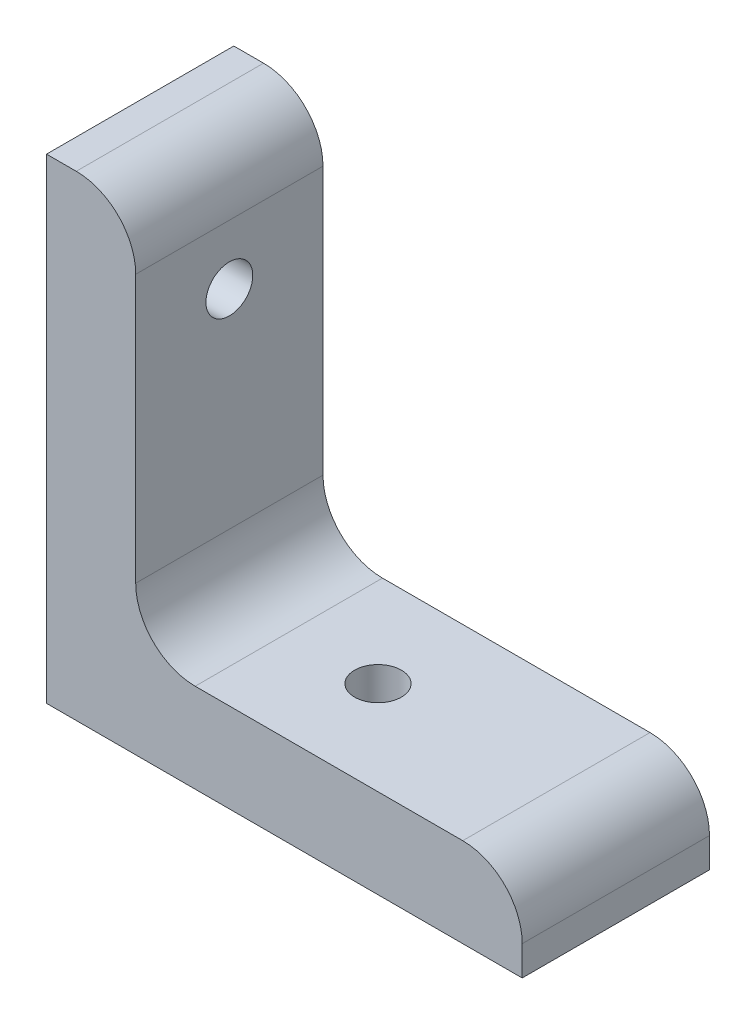
SolidWorks part; units mm, degrees
ref_plane "Front Plane" through (0, 0, 0) normal (0, 0, 1) x (1, 0, 0)
ref_plane "Top Plane" through (0, 0, 0) normal (0, 1, 0) x (1, 0, 0)
ref_plane "Right Plane" through (0, 0, 0) normal (1, 0, 0) x (0, 0, -1)
sketch "Sketch1" plane through (0, 0, 0) normal (0, 0, 1) x (1, 0, 0)
  line L0 (0, 0) -> (0, 50.8)
  line L1 (0, 50.8) -> (9.525, 50.8)
  line L2 (9.525, 50.8) -> (9.525, 9.525)
  line L3 (9.525, 9.525) -> (50.8, 9.525)
  line L4 (50.8, 9.525) -> (50.8, 0)
  line L5 (50.8, 0) -> (0, 0)
  dimension "D1" = 50.8
  dimension "D2" = 50.8
  dimension "D3" = 9.525
  dimension "D4" = 9.525
extrude "Boss-Extrude1" add sketch "Sketch1" against normal blind 20
fillet "Fillet1" radius 6.35 3 edges at (9.525, 9.525, -10) (9.525, 50.8, -10) (50.8, 9.525, -10)
hole_wizard "Ø5.0mm Dowel Hole1" positions "Sketch2" profile "Sketch3" hole size "Ø5.0" standard "ANSI Metric" end condition through all
sketch "Sketch2" plane through (0, 0, 0) normal (0, -1, 0) x (-1, 0, 0)
  line L0 (0, 20) -> (0, 0) construction
  line L1 (0, 0) -> (-50.8, 0) construction
  point P0 (-25.4, 10)
  dimension "D1" = 25.4
  dimension "D2" = 10
sketch "Sketch3" plane through (25.4, 0, -10) normal (1, 0, 0) x (0, 0, -1)
  line L0 (0, 0) -> (0, 50.8)
  line L1 (0, 50.8) -> (2.5, 50.8)
  line L2 (2.5, 50.8) -> (2.5, 0)
  line L5 (2.5, 0) -> (0, 0)
  line L11 (0, -6.35) -> (0, 107.95) construction
  dimension "Thru Hole Dia." = 5
  dimension "Thru Hole Depth" = 50.8
hole_wizard "Ø5.0mm Dowel Hole2" positions "Sketch4" profile "Sketch5" hole size "Ø5.0" standard "ANSI Metric" end condition through all
sketch "Sketch4" plane through (0, 0, 0) normal (-1, 0, 0) x (0, 0, 1)
  line L0 (0, 50.8) -> (0, 0) construction
  line L1 (-20, 0) -> (0, 0) construction
  point P0 (-10, 38.1)
  dimension "D1" = 10
  dimension "D2" = 38.1
sketch "Sketch5" plane through (0, 38.1, -10) normal (0, 1, 0) x (0, 0, 1)
  line L0 (0, 0) -> (0, 50.8)
  line L1 (0, 50.8) -> (2.5, 50.8)
  line L2 (2.5, 50.8) -> (2.5, 0)
  line L5 (2.5, 0) -> (0, 0)
  line L11 (0, -6.35) -> (0, 107.95) construction
  dimension "Thru Hole Dia." = 5
  dimension "Thru Hole Depth" = 50.8
